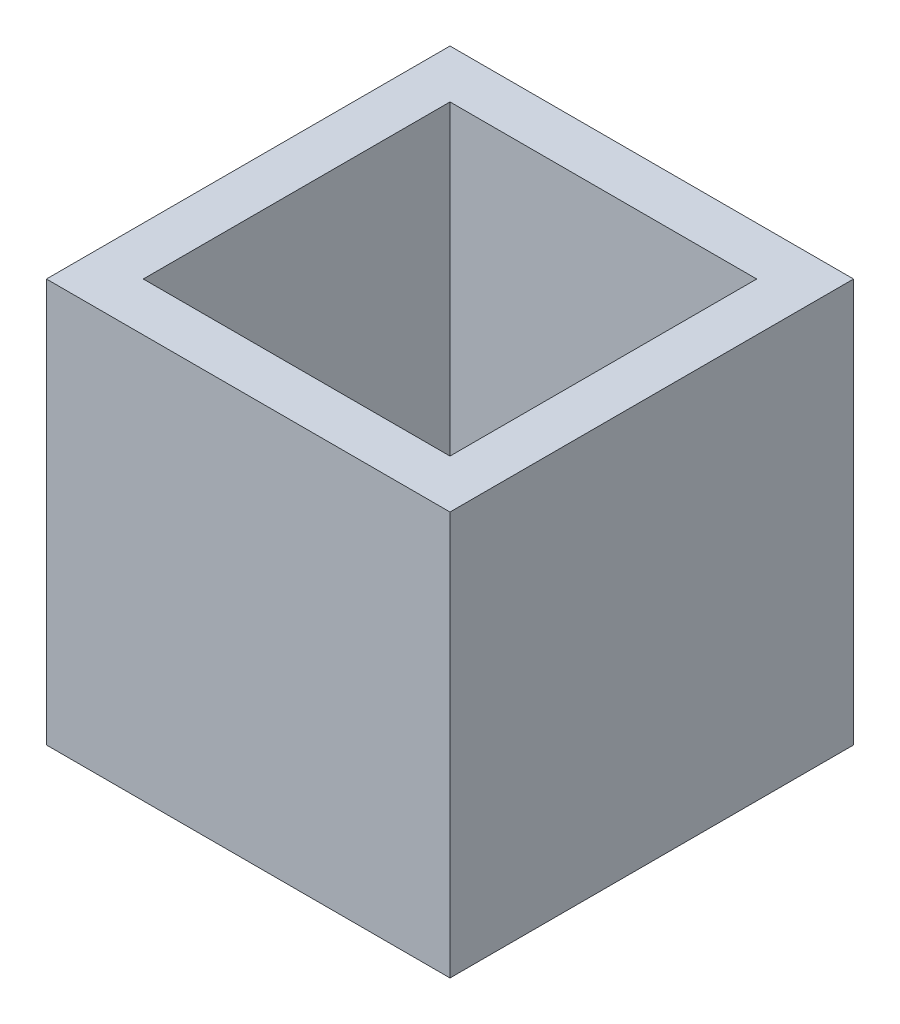
SolidWorks part; units mm, degrees
ref_plane "Front" through (0, 0, 0) normal (0, 0, 1) x (1, 0, 0)
ref_plane "Top" through (0, 0, 0) normal (0, 1, 0) x (1, 0, 0)
ref_plane "Right" through (0, 0, 0) normal (1, 0, 0) x (0, 0, -1)
sketch "Sketch1" plane through (0, 0, 0) normal (0, 1, 0) x (1, 0, 0)
  line L1 (-12.5, -12.5) -> (12.5, -12.5)
  line L2 (-12.5, -12.5) -> (-12.5, 12.5)
  line L3 (-12.5, 12.5) -> (12.5, 12.5)
  line L4 (12.5, -12.5) -> (12.5, 12.5)
  line L5 (-12.5, -12.5) -> (12.5, 12.5) construction
  line L6 (-12.5, 12.5) -> (12.5, -12.5) construction
  point P0 (0, 0)
  dimension "D1" = 25
  dimension "D2" = 25
extrude "Boss-Extrude1" add sketch "Sketch1" along normal blind 25 contours L3 L4 L1 L2
shell "Shell1" thickness 3
sketch "Sketch2" plane through (0, 0, 0) normal (0, -1, 0) x (1, 0, 0)
  line L0 (-9.5, -9.5) -> (9.5, -9.5) construction
  line L1 (9.5, 9.5) -> (9.5, -9.5) construction
  line L2 (-9.5, 9.5) -> (9.5, 9.5) construction
  line L3 (-9.5, 9.5) -> (-9.5, -9.5) construction
  line L4 (-9.5, -9.5) -> (9.5, -9.5)
  line L5 (9.5, 9.5) -> (9.5, -9.5)
  line L6 (-9.5, 9.5) -> (9.5, 9.5)
  line L7 (-9.5, 9.5) -> (-9.5, -9.5)
sketch "Sketch3" plane through (0, 25, 0) normal (0, 1, 0) x (1, 0, 0)
  line L4 (9.5, 9.5) -> (-9.5, 9.5)
  line L5 (9.5, -9.5) -> (9.5, 9.5)
  line L6 (-9.5, -9.5) -> (9.5, -9.5)
  line L7 (-9.5, 9.5) -> (-9.5, -9.5)
  line L8 (9.5, 9.5) -> (-9.5, 9.5)
  line L9 (9.5, -9.5) -> (9.5, 9.5)
  line L10 (-9.5, -9.5) -> (9.5, -9.5)
  line L11 (-9.5, 9.5) -> (-9.5, -9.5)
  dimension "D1" = 0
extrude "Cut-Extrude2" cut sketch "Sketch3" against normal blind 17
